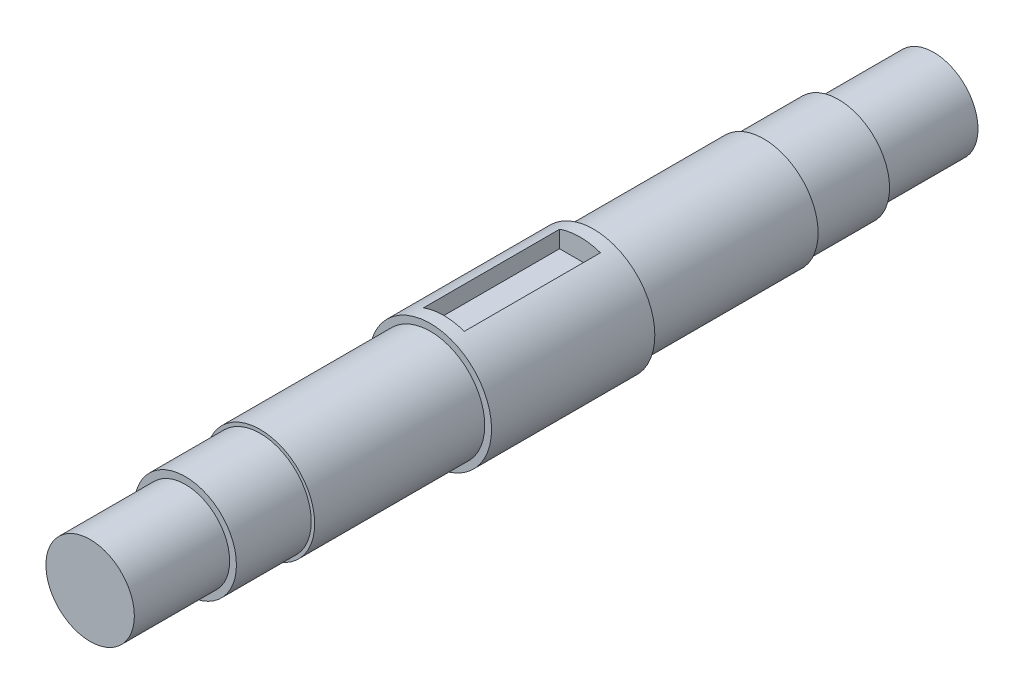
SolidWorks part; units mm, degrees
material "Plain Carbon Steel"
ref_plane "Front Plane" through (0, 0, 0) normal (1, 0, 0) x (0, 1, 0)
ref_plane "Top Plane" through (0, 0, 0) normal (0, 0, 1) x (0, 1, 0)
ref_plane "Right Plane" through (0, 0, 0) normal (0, 1, 0) x (-1, 0, 0)
sketch "Sketch1" plane through (0, 0, 0) normal (0, 0, 1) x (0, 1, 0)
  circle A0 centre (0, 0) radius 6.5
  dimension "D1" = 13
extrude "Boss-Extrude1" add sketch "Sketch1" along normal blind 14
sketch "Sketch2" plane through (0, 0, 14) normal (0, 0, 1) x (1, 0, 0)
  circle A0 centre (0, 0) radius 7.5
  dimension "D1" = 15
extrude "Boss-Extrude2" add sketch "Sketch2" along normal blind 11
sketch "Sketch3" plane through (0, 0, 25) normal (0, 0, 1) x (1, 0, 0)
  circle A0 centre (0, 0) radius 8
  dimension "D1" = 16
extrude "Boss-Extrude3" add sketch "Sketch3" along normal blind 25
sketch "Sketch4" plane through (0, 0, 50) normal (0, 0, 1) x (1, 0, 0)
  circle A0 centre (0, 0) radius 9
  dimension "D1" = 18
extrude "Boss-Extrude4" add sketch "Sketch4" along normal blind 12
ref_plane "Plane1" through (0, 0, 62) normal (0, 0, 1) x (0, -1, 0)
mirror "Mirror1" about plane through (0, 0, 62) normal (0, 0, 1) of bodies 104
ref_plane "Plane2" through (0, 9, 0) normal (0, 1, 0) x (-1, 0, 0)
sketch "Sketch5" plane through (0, 9, 0) normal (0, 1, 0) x (-1, 0, 0)
  line L0 (55, 62) -> (-55, 62) construction
  line L1 (-3, 72) -> (3, 72)
  line L2 (-3, 72) -> (-3, 52)
  line L3 (-3, 52) -> (3, 52)
  line L4 (3, 72) -> (3, 52)
  line L5 (-3, 72) -> (3, 52) construction
  line L6 (-3, 52) -> (3, 72) construction
  point P0 (0, 62)
  point P7 (-15.8745, 62)
  point P9 (0.7737, 62)
  dimension "D1" = 3
  dimension "D2" = 20
  dimension "D3" = 6
extrude "Cut-Extrude2" cut sketch "Sketch5" against normal blind 3
